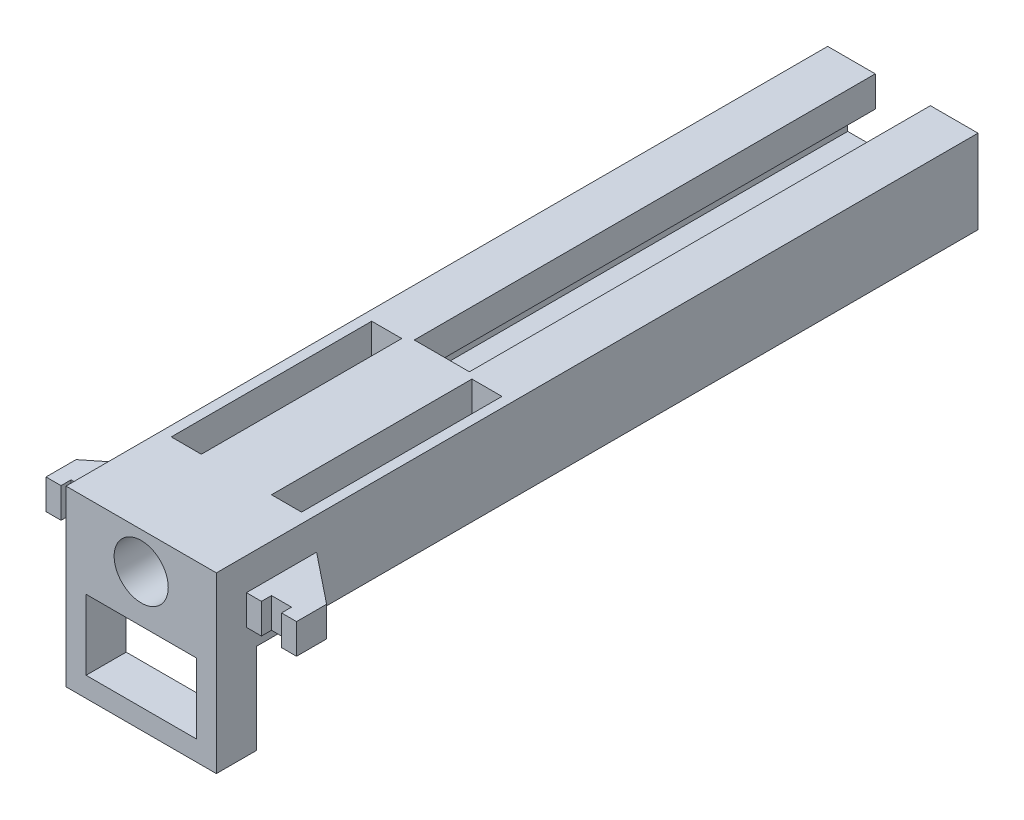
SolidWorks part; units mm, degrees
ref_plane "Front Plane" through (0, 0, 0) normal (0, 0, 1) x (1, 0, 0)
ref_plane "Top Plane" through (0, 0, 0) normal (0, 1, 0) x (1, 0, 0)
ref_plane "Right Plane" through (0, 0, 0) normal (1, 0, 0) x (0, 0, -1)
sketch "Sketch9" plane through (0, 0, 0) normal (0, 0, 1) x (1, 0, 0)
  line L1 (-7.5, 8.35) -> (7.5, 8.35)
  line L2 (-7.5, 8.35) -> (-7.5, 0)
  line L3 (-7.5, 0) -> (7.5, 0)
  line L4 (7.5, 8.35) -> (7.5, 0)
  line L5 (-7.5, 8.35) -> (7.5, 0) construction
  line L6 (-7.5, 0) -> (7.5, 8.35) construction
  point P0 (0, 4.175)
  point P19 (0, 0)
  dimension "D1" = 8.35
  dimension "D2" = 15
extrude "Boss-Extrude4" add sketch "Sketch9" along normal blind 76
sketch "Sketch7" plane through (0, 0, 0) normal (0, 0, 1) x (1, 0, 0)
  line L0 (-5.5, 2) -> (-5.5, 5.3)
  line L1 (-5.5, 5.3) -> (-2.75, 5.3)
  line L2 (-2.75, 5.3) -> (-2.75, 8.35)
  line L3 (-2.75, 8.35) -> (2.75, 8.35) construction
  line L4 (2.75, 8.35) -> (2.75, 5.3)
  line L5 (2.75, 5.3) -> (5.5, 5.3)
  line L6 (5.5, 5.3) -> (5.5, 2)
  line L7 (5.5, 2) -> (-5.5, 2)
  line L9 (7.5, 8.35) -> (-7.5, 8.35) construction
  line L11 (7.5, 0) -> (7.5, 8.35) construction
  line L13 (-2.75, 8.35) -> (2.75, 8.35)
  dimension "D1" = 3.3
  dimension "D2" = 2
  dimension "D3" = 11
  dimension "D4" = 5.5
  dimension "D5" = 2
extrude "Cut-Extrude4" cut sketch "Sketch7" along normal blind 46
sketch "Sketch10" plane through (0, 0, 76) normal (0, 0, 1) x (1, 0, 0)
  line L0 (5.5, 2) -> (-5.5, 2) construction
  circle A0 centre (0, 4.7) radius 2.7
  dimension "D1" = 5.4
extrude "Cut-Extrude5" cut sketch "Sketch10" against normal up to surface (30 mm away) up to face at (0, 5.2375, 46)
sketch "Sketch12" plane through (7.5, 0, 0) normal (1, 0, 0) x (0, 0, -1)
  line L0 (-76, 0) -> (0, 0) construction
  line L1 (-73, 5.14) -> (-70, 5.14)
  line L2 (-73, 5.14) -> (-73, 2.14)
  line L3 (-73, 2.14) -> (-70, 2.14)
  line L4 (-70, 5.14) -> (-70, 2.14)
  line L5 (-73, 5.14) -> (-70, 2.14) construction
  line L6 (-73, 2.14) -> (-70, 5.14) construction
  line L7 (-76, 0) -> (-76, 8.35) construction
  point P0 (-71.5, 3.64)
  dimension "D1" = 3
  dimension "D2" = 3
  dimension "D3" = 2.14
  dimension "D4" = 3
extrude "Boss-Extrude5" add sketch "Sketch12" along normal blind 5
ref_plane "Plane1" through (0, 0, 0) normal (1, 0, 0) x (0, 0, -1)
sketch "Sketch13" plane through (0, 0, 73) normal (0, 0, 1) x (1, 0, 0)
  line L1 (9, 5.14) -> (11, 5.14)
  line L2 (9, 5.14) -> (9, 2.14)
  line L3 (9, 2.14) -> (11, 2.14)
  line L4 (11, 5.14) -> (11, 2.14)
  line L6 (12.5, 5.14) -> (7.5, 5.14) construction
  line L7 (12.5, 2.14) -> (7.5, 2.14) construction
  point P8 (10, 5.14)
  point P9 (10, 5.14)
  dimension "D2" = 2
extrude "Cut-Extrude6" cut sketch "Sketch13" against normal blind 1
mirror "Mirror2" about plane through (0, 0, 0) normal (1, 0, 0) of "Boss-Extrude5"
mirror "Mirror4" about plane through (0, 0, 0) normal (1, 0, 0) of "Cut-Extrude6"
sketch "Sketch14" plane through (0, 5.14, 0) normal (0, 1, 0) x (1, 0, 0)
  line L0 (12.5, -70) -> (7.5, -66)
  line L1 (7.5, -76) -> (7.5, 0) construction
  line L2 (7.5, -66) -> (7.5, -70)
  line L3 (7.5, -70) -> (12.5, -70)
  dimension "D1" = 4
extrude "Boss-Extrude6" add sketch "Sketch14" against normal up to surface (3 mm away) up to face at (10, 2.14, 72)
mirror "Mirror5" about plane through (0, 0, 0) normal (1, 0, 0) of "Boss-Extrude6"
sketch "Sketch15" plane through (0, 8.35, 0) normal (0, 1, 0) x (1, 0, 0)
  line L0 (-7.5, -76) -> (-7.5, 0) construction
  line L1 (-6.5, -66.5) -> (-3.5, -66.5)
  line L2 (-6.5, -66.5) -> (-6.5, -46.5)
  line L3 (-6.5, -46.5) -> (-3.5, -46.5)
  line L4 (-3.5, -66.5) -> (-3.5, -46.5)
  line L5 (-6.5, -66.5) -> (-3.5, -46.5) construction
  line L6 (-6.5, -46.5) -> (-3.5, -66.5) construction
  line L7 (2.75, -46) -> (-2.75, -46) construction
  point P0 (-5, -56.5)
  point P11 (-5, -46.5)
  dimension "D1" = 20
  dimension "D2" = 3
  dimension "D3" = 1
  dimension "D4" = 0.5
extrude "Cut-Extrude7" cut sketch "Sketch15" against normal up to next
mirror "Mirror6" about plane through (0, 0, 0) normal (1, 0, 0) of "Cut-Extrude7"
sketch "Sketch16" plane through (0, 0, 0) normal (0, -1, 0) x (1, 0, 0)
  line L0 (0, -35.8636) -> (0, 35.8636) construction
  line L1 (-7.5, 76) -> (7.5, 76) construction
  circle A0 centre (0, 69) radius 2.5
  dimension "D1" = 5
  dimension "D2" = 7
extrude "Cut-Extrude8" cut sketch "Sketch16" against normal up to surface (2 mm away)
sketch "Sketch17" plane through (0, 0, 0) normal (0, -1, 0) x (1, 0, 0)
  line L1 (-7.5, 76) -> (7.5, 76) construction
  line L2 (0, 76) -> (0, 0) construction
  line L3 (-7.5, 76) -> (-7.5, 0) construction
  circle A0 centre (-3, 73.5) radius 1.5
  circle A1 centre (3, 73.5) radius 1.5
  dimension "D1" = 3
  dimension "D2" = 4.5
  dimension "D3" = 2.5
extrude "Boss-Extrude7" [suppressed] add sketch "Sketch17" along normal up to surface (9 mm away)
sketch "Sketch18" plane through (0, 0, 76) normal (0, 0, 1) x (1, 0, 0)
  line L7 (-7.5, 0) -> (7.5, 0) construction
  line L9 (-7.5, 4.175) -> (7.5, 4.175) construction
  line L10 (-7.5, 8.35) -> (-7.5, 0) construction
  line L11 (7.5, 0) -> (7.5, 8.35) construction
  line L12 (-5.5, 0) -> (-7.5, 0)
  line L13 (-5.5, -7) -> (-5.5, 0)
  line L14 (5.5, -7) -> (-5.5, -7)
  line L15 (5.5, 0) -> (5.5, -7)
  line L16 (7.5, 0) -> (5.5, 0)
  line L17 (7.5, -9) -> (7.5, 0)
  line L18 (-7.5, -9) -> (7.5, -9)
  line L19 (-7.5, 0) -> (-7.5, -9)
  dimension "D1" = 2
  dimension "D2" = 2
  dimension "D3" = 9
extrude "Boss-Extrude8" add sketch "Sketch18" against normal blind 4
